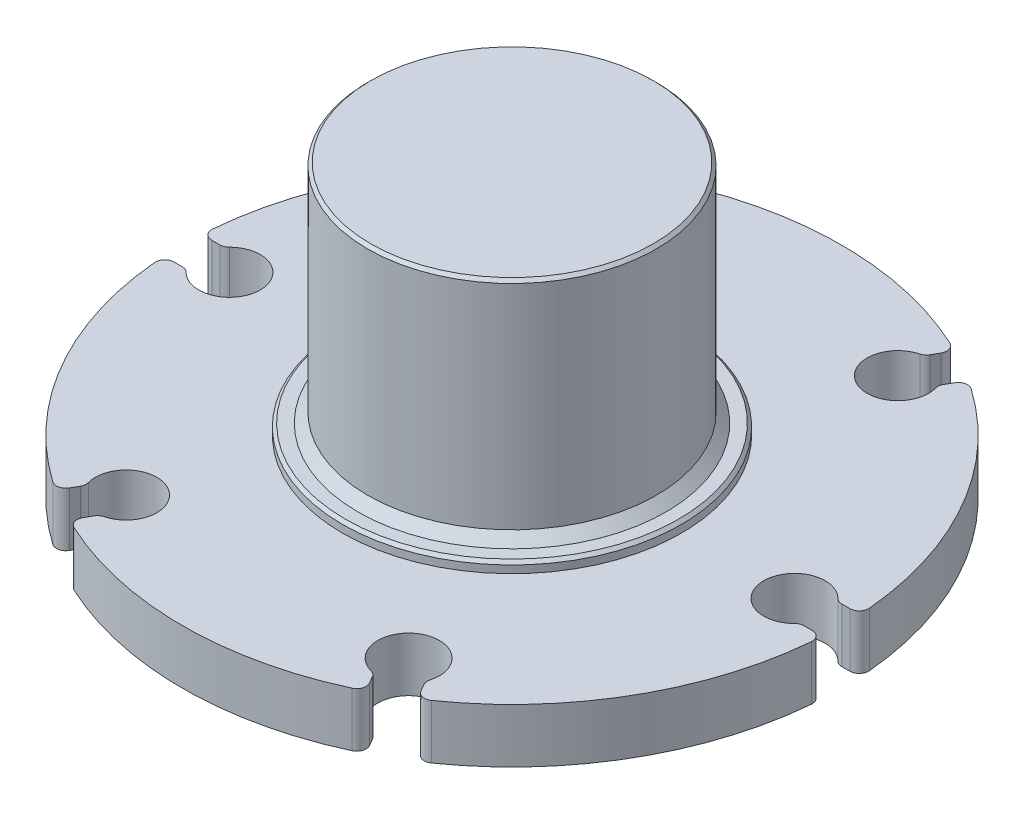
SolidWorks part; units mm, degrees
ref_plane "Front Plane" through (0, 0, 0) normal (0, 0, 1) x (1, 0, 0)
ref_plane "Top Plane" through (0, 0, 0) normal (0, 1, 0) x (1, 0, 0)
ref_plane "Right Plane" through (0, 0, 0) normal (1, 0, 0) x (0, 0, -1)
sketch "Sketch1" plane through (0, 0, 0) normal (0, 0, 1) x (1, 0, 0)
  line L0 (27.7876, 5.461) -> (0, 5.461)
  line L1 (0, 5.461) -> (0, 0.889)
  line L2 (0, 0.889) -> (27.7876, 0.889)
  line L3 (27.7876, 0.889) -> (27.7876, 5.461)
  line L4 (0, 5.461) -> (0, 0.889) construction
revolve "Revolve1" add sketch "Sketch1" angle 360 about L4
sketch "Sketch2" plane through (0, 0.889, 0) normal (0, -1, 0) x (1, 0, 0)
  line L0 (-27.7422, -1.5875) -> (-25.86, -1.5875)
  line L1 (-25.86, 1.5875) -> (-27.7422, 1.5875)
  arc A0 (-27.7422, 1.5875) -> (-27.7422, -1.5875) centre (0, 0) ccw
  arc A1 (-25.86, -1.5875) -> (-25.86, 1.5875) centre (-23.8125, 0) cw
extrude "Cut-Extrude1" cut sketch "Sketch2" against normal through all
sketch "Sketch3" plane through (0, 0.889, 0) normal (0, -1, 0) x (1, 0, 0)
  line L0 (-15.2459, 23.2317) -> (-14.3048, 21.6016)
  line L1 (-11.5552, 23.1891) -> (-12.4963, 24.8192)
  arc A0 (-12.4963, 24.8192) -> (-15.2459, 23.2317) centre (0, 0) ccw
  arc A1 (-14.3048, 21.6016) -> (-11.5552, 23.1891) centre (-11.9062, 20.6222) cw
extrude "Cut-Extrude2" cut sketch "Sketch3" against normal through all
sketch "Sketch4" plane through (0, 0.889, 0) normal (0, -1, 0) x (1, 0, 0)
  line L0 (12.4963, 24.8192) -> (11.5552, 23.1891)
  line L1 (14.3048, 21.6016) -> (15.2459, 23.2317)
  arc A0 (15.2459, 23.2317) -> (12.4963, 24.8192) centre (0, 0) ccw
  arc A1 (11.5552, 23.1891) -> (14.3048, 21.6016) centre (11.9063, 20.6222) cw
extrude "Cut-Extrude3" cut sketch "Sketch4" against normal through all
sketch "Sketch5" plane through (0, 0.889, 0) normal (0, -1, 0) x (1, 0, 0)
  line L0 (27.7422, 1.5875) -> (25.86, 1.5875)
  line L1 (25.86, -1.5875) -> (27.7422, -1.5875)
  arc A0 (27.7422, -1.5875) -> (27.7422, 1.5875) centre (0, 0) ccw
  arc A1 (25.86, 1.5875) -> (25.86, -1.5875) centre (23.8125, 0) cw
extrude "Cut-Extrude4" cut sketch "Sketch5" against normal through all
sketch "Sketch6" plane through (0, 0.889, 0) normal (0, -1, 0) x (1, 0, 0)
  line L0 (15.2459, -23.2317) -> (14.3048, -21.6016)
  line L1 (11.5552, -23.1891) -> (12.4963, -24.8192)
  arc A0 (12.4963, -24.8192) -> (15.2459, -23.2317) centre (0, 0) ccw
  arc A1 (14.3048, -21.6016) -> (11.5552, -23.1891) centre (11.9062, -20.6222) cw
extrude "Cut-Extrude5" cut sketch "Sketch6" against normal through all
sketch "Sketch7" plane through (0, 0.889, 0) normal (0, -1, 0) x (1, 0, 0)
  line L0 (-12.4963, -24.8192) -> (-11.5552, -23.1891)
  line L1 (-14.3048, -21.6016) -> (-15.2459, -23.2317)
  arc A0 (-15.2459, -23.2317) -> (-12.4963, -24.8192) centre (0, 0) ccw
  arc A1 (-11.5552, -23.1891) -> (-14.3048, -21.6016) centre (-11.9063, -20.6222) cw
extrude "Cut-Extrude6" cut sketch "Sketch7" against normal through all
sketch "Sketch8" plane through (0, 5.461, 0) normal (0, 1, 0) x (-1, 0, 0)
  circle A0 centre (0, 0) radius 14.2875
extrude "Boss-Extrude1" add sketch "Sketch8" along normal blind 0.889
sketch "Sketch9" plane through (0, 6.35, 0) normal (0, 1, 0) x (-1, 0, 0)
  circle A0 centre (0, 0) radius 12.9794
extrude "Boss-Extrude2" add sketch "Sketch9" along normal blind 0.8128 draft 45
sketch "Sketch10" plane through (0, 7.1628, 0) normal (0, 1, 0) x (-1, 0, 0)
  circle A0 centre (0, 0) radius 12.1666
extrude "Boss-Extrude3" add sketch "Sketch10" along normal blind 18.2372
sketch "Sketch11" plane through (0, 0.889, 0) normal (0, -1, 0) x (1, 0, 0)
  circle A0 centre (0, 0) radius 14.2875
extrude "Boss-Extrude4" add sketch "Sketch11" along normal blind 0.889
sketch "Sketch12" plane through (0, 0, 0) normal (0, -1, 0) x (1, 0, 0)
  line L0 (-8.0518, -1.6573) -> (-6.2482, -1.6573)
  line L1 (6.2482, -1.6573) -> (8.0518, -1.6573)
  line L2 (8.0518, -1.6573) -> (8.0518, 1.6573)
  line L3 (8.0518, 1.6573) -> (6.2482, 1.6573)
  line L4 (-6.2482, 1.6573) -> (-8.0518, 1.6573)
  line L5 (-8.0518, 1.6573) -> (-8.0518, -1.6573)
  arc A0 (-6.2482, -1.6573) -> (6.2482, -1.6573) centre (0, 0) ccw
  arc A1 (6.2482, 1.6573) -> (-6.2482, 1.6573) centre (0, 0) ccw
extrude "Cut-Extrude7" cut sketch "Sketch12" against normal through all
sketch "Sketch13" plane through (0, 0, 0) normal (0, 0, 1) x (1, 0, 0)
  line L0 (-21.2217, 5.461) -> (-23.8125, 5.461)
  line L1 (-23.8125, 5.461) -> (-23.8125, 0.889)
  line L2 (-23.8125, 0.889) -> (-21.2217, 0.889)
  line L3 (-21.2217, 0.889) -> (-21.2217, 5.461)
  line L4 (-23.8125, 5.461) -> (-23.8125, 0.889) construction
revolve "Cut-Revolve1" cut sketch "Sketch13" angle 360 about L4
ref_plane "Plane1" through (0, 0, 20.6222) normal (0, 0, -1) x (-1, 0, 0)
sketch "Sketch14" plane through (0, 0, 20.6222) normal (0, 0, -1) x (-1, 0, 0)
  line L0 (9.3154, 0.889) -> (11.9062, 0.889)
  line L1 (11.9062, 0.889) -> (11.9062, 5.461)
  line L2 (11.9062, 5.461) -> (9.3154, 5.461)
  line L3 (9.3154, 5.461) -> (9.3154, 0.889)
  line L4 (11.9062, 0.889) -> (11.9062, 5.461) construction
revolve "Cut-Revolve2" cut sketch "Sketch14" angle 360 about L4
sketch "Sketch15" plane through (0, 0, 20.6222) normal (0, 0, -1) x (-1, 0, 0)
  line L0 (-14.4971, 0.889) -> (-11.9063, 0.889)
  line L1 (-11.9063, 0.889) -> (-11.9063, 5.461)
  line L2 (-11.9063, 5.461) -> (-14.4971, 5.461)
  line L3 (-14.4971, 5.461) -> (-14.4971, 0.889)
  line L4 (-11.9063, 0.889) -> (-11.9063, 5.461) construction
revolve "Cut-Revolve3" cut sketch "Sketch15" angle 360 about L4
sketch "Sketch16" plane through (0, 0, 0) normal (0, 0, 1) x (1, 0, 0)
  line L0 (26.4033, 5.461) -> (23.8125, 5.461)
  line L1 (23.8125, 5.461) -> (23.8125, 0.889)
  line L2 (23.8125, 0.889) -> (26.4033, 0.889)
  line L3 (26.4033, 0.889) -> (26.4033, 5.461)
  line L4 (23.8125, 5.461) -> (23.8125, 0.889) construction
revolve "Cut-Revolve4" cut sketch "Sketch16" angle 360 about L4
ref_plane "Plane2" through (0, 0, -20.6222) normal (0, 0, 1) x (1, 0, 0)
sketch "Sketch17" plane through (0, 0, -20.6222) normal (0, 0, 1) x (1, 0, 0)
  line L0 (14.497, 5.461) -> (11.9062, 5.461)
  line L1 (11.9062, 5.461) -> (11.9062, 0.889)
  line L2 (11.9062, 0.889) -> (14.497, 0.889)
  line L3 (14.497, 0.889) -> (14.497, 5.461)
  line L4 (11.9062, 5.461) -> (11.9062, 0.889) construction
revolve "Cut-Revolve5" cut sketch "Sketch17" angle 360 about L4
sketch "Sketch18" plane through (0, 0, -20.6222) normal (0, 0, 1) x (1, 0, 0)
  line L0 (-9.3155, 5.461) -> (-11.9063, 5.461)
  line L1 (-11.9063, 5.461) -> (-11.9063, 0.889)
  line L2 (-11.9063, 0.889) -> (-9.3155, 0.889)
  line L3 (-9.3155, 0.889) -> (-9.3155, 5.461)
  line L4 (-11.9063, 5.461) -> (-11.9063, 0.889) construction
revolve "Cut-Revolve6" cut sketch "Sketch18" angle 360 about L4
chamfer "Chamfer1" distance 0.254 angle 45 7 edges at (0, 0, 6.4643) (0, 6.35, 14.2875) (0, 0, -14.2875) (0, 0, -6.4643) (0, 25.4, 12.1666) (0, 25.4, -6.4643) (0, 25.4, 6.4643)
fillet "Fillet1" radius 0.127 8 edges at (-6.2482, 12.7, 1.6574) (-8.0518, 12.7, 1.6573) (-8.0518, 12.7, -1.6573) (6.2482, 12.7, 1.6573) (-6.2482, 12.7, -1.6573) (8.0518, 12.7, 1.6573) (8.0518, 12.7, -1.6573) (6.2482, 12.7, -1.6574)
fillet "Fillet2" radius 0.7874 24 edges at (-12.4963, 3.175, 24.8192) (-15.2459, 3.175, -23.2317) (-27.7422, 3.175, 1.5875) (-14.3048, 3.175, -21.6016) (14.3048, 3.175, 21.6016) (-11.5552, 3.175, -23.1891) (-11.5552, 3.175, 23.1891) (-12.4963, 3.175, -24.8192) (-25.86, 3.175, -1.5875) (12.4963, 3.175, -24.8192) (11.5552, 3.175, 23.1891) (14.3048, 3.175, -21.6016) (12.4963, 3.175, 24.8192) (15.2459, 3.175, -23.2317) (-14.3048, 3.175, 21.6016) (27.7422, 3.175, -1.5875) (-15.2459, 3.175, 23.2317) (25.86, 3.175, -1.5875) (-25.86, 3.175, 1.5875) (25.86, 3.175, 1.5875) (-27.7422, 3.175, -1.5875) (27.7422, 3.175, 1.5875) (15.2459, 3.175, 23.2317) (11.5552, 3.175, -23.1891)
sketch "Sketch19" plane through (0, 25.4, 0) normal (0, 1, 0) x (1, 0, 0)
  circle A0 centre (0, 0) radius 9.3504
extrude "Boss-Extrude7" add sketch "Sketch19" against normal blind 25.4 contours A0
